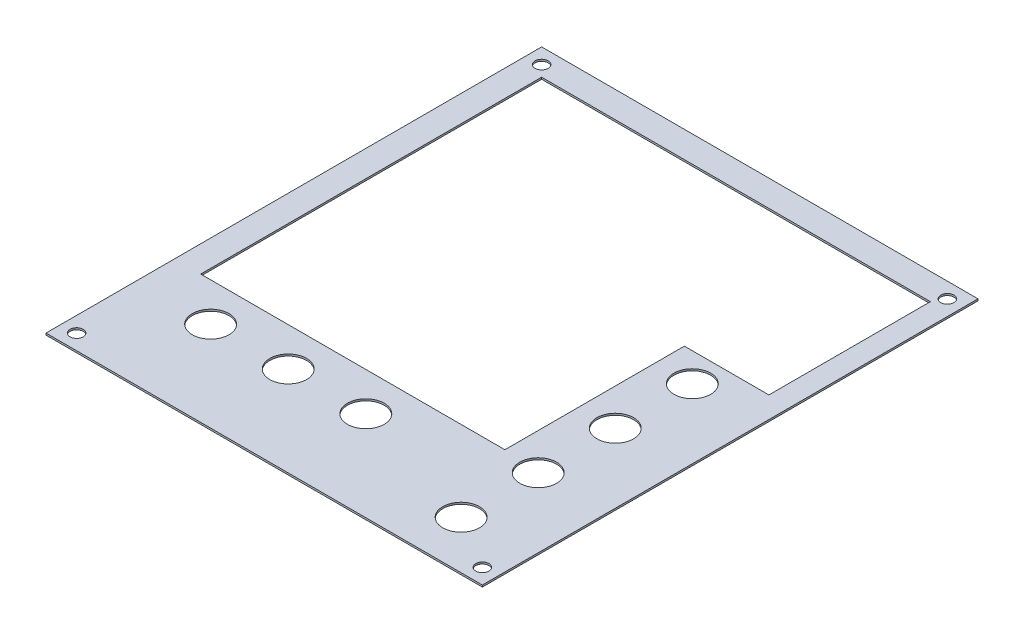
SolidWorks part; units mm, degrees
ref_plane "Front Plane" through (0, 0, 0) normal (0, 0, 1) x (1, 0, 0)
ref_plane "Top Plane" through (0, 0, 0) normal (0, 1, 0) x (1, 0, 0)
ref_plane "Right Plane" through (0, 0, 0) normal (1, 0, 0) x (0, 0, -1)
sketch "Sketch1" plane through (0, 0, 0) normal (0, 1, 0) x (1, 0, 0)
  line L0 (11.302, 19.99) -> (11.302, 8.49) construction
  line L1 (0, 0) -> (77.34, 0) construction
  line L2 (0, 0) -> (0, 88.64) construction
  line L3 (0, 88.64) -> (77.34, 88.64) construction
  line L4 (77.34, 0) -> (77.34, 88.64) construction
  line L5 (6.302, 8.49) -> (16.302, 8.49) construction
  line L6 (6.302, 8.49) -> (6.302, 19.99) construction
  line L7 (6.302, 19.99) -> (16.302, 19.99) construction
  line L8 (16.302, 8.49) -> (16.302, 19.99) construction
  line L9 (21.095, 8.49) -> (31.095, 8.49) construction
  line L10 (21.095, 8.49) -> (21.095, 19.99) construction
  line L11 (21.095, 19.99) -> (31.095, 19.99) construction
  line L12 (31.095, 8.49) -> (31.095, 19.99) construction
  line L13 (35.888, 8.49) -> (45.888, 8.49) construction
  line L14 (35.888, 8.49) -> (35.888, 19.99) construction
  line L15 (35.888, 19.99) -> (45.888, 19.99) construction
  line L16 (45.888, 8.49) -> (45.888, 19.99) construction
  line L17 (62.147, 30.178) -> (71.947, 30.178) construction
  line L18 (62.147, 30.178) -> (62.147, 41.078) construction
  line L19 (62.147, 41.078) -> (71.947, 41.078) construction
  line L20 (71.947, 30.178) -> (71.947, 41.078) construction
  line L21 (62.147, 15.488) -> (71.947, 15.488) construction
  line L22 (62.147, 15.488) -> (62.147, 26.388) construction
  line L23 (62.147, 26.388) -> (71.947, 26.388) construction
  line L24 (71.947, 15.488) -> (71.947, 26.388) construction
  line L25 (62.147, 0.798) -> (71.947, 0.798) construction
  line L26 (62.147, 0.798) -> (62.147, 11.698) construction
  line L27 (62.147, 11.698) -> (71.947, 11.698) construction
  line L28 (71.947, 0.798) -> (71.947, 11.698) construction
  line L29 (62.147, 44.868) -> (71.947, 44.868) construction
  line L30 (62.147, 44.868) -> (62.147, 55.768) construction
  line L31 (62.147, 55.768) -> (71.947, 55.768) construction
  line L32 (71.947, 44.868) -> (71.947, 55.768) construction
  line L33 (26.095, 19.99) -> (26.095, 8.49) construction
  line L34 (40.888, 19.99) -> (40.888, 8.49) construction
  line L35 (67.047, 11.698) -> (67.047, 0.798) construction
  line L36 (67.047, 26.388) -> (67.047, 15.488) construction
  line L37 (67.047, 41.078) -> (67.047, 30.178) construction
  line L38 (67.047, 55.768) -> (67.047, 44.868) construction
  line L40 (-2.92, 91.56) -> (80.26, 91.56)
  line L41 (-2.92, 91.56) -> (-2.92, -2.92)
  line L42 (-2.92, -2.92) -> (80.26, -2.92)
  line L43 (80.26, 91.56) -> (80.26, -2.92)
  line L44 (2.08, 86.56) -> (60.08, 86.56)
  line L45 (2.08, 86.56) -> (2.08, 21.56)
  line L46 (2.08, 21.56) -> (60.08, 21.56)
  line L47 (60.08, 55.768) -> (60.08, 21.56)
  line L48 (60.08, 86.56) -> (76.1929, 86.56)
  line L50 (60.08, 55.768) -> (76.1929, 55.768)
  line L51 (76.1929, 86.56) -> (76.1929, 55.768)
  circle A0 centre (0, 88.64) radius 1.25
  circle A1 centre (77.34, 88.64) radius 1.25
  circle A2 centre (77.34, 0) radius 1.25
  circle A3 centre (0, 0) radius 1.25
  circle A4 centre (11.302, 14.24) radius 3.5
  circle A5 centre (26.095, 14.24) radius 3.5
  circle A6 centre (40.888, 14.24) radius 3.5
  circle A7 centre (67.047, 6.248) radius 3.5
  circle A8 centre (67.047, 20.938) radius 3.5
  circle A9 centre (67.047, 35.628) radius 3.5
  circle A10 centre (67.047, 50.318) radius 3.5
  dimension "D3" = 2.5
  dimension "D4" = 2.5
  dimension "D5" = 2.5
  dimension "D6" = 2.5
  dimension "D30" = 7
  dimension "D31" = 7
  dimension "D32" = 7
  dimension "D33" = 7
  dimension "D34" = 7
  dimension "D35" = 7
  dimension "D36" = 7
  dimension "D37" = 2.92
  dimension "D38" = 2.92
  dimension "D39" = 2.92
  dimension "D40" = 2.92
  dimension "D1" = 88.64
  dimension "D2" = 77.34
  dimension "D7" = 10
  dimension "D8" = 11.5
  dimension "D9" = 10
  dimension "D10" = 11.5
  dimension "D11" = 10
  dimension "D12" = 11.5
  dimension "D13" = 4.793
  dimension "D14" = 4.793
  dimension "D15" = 6.302
  dimension "D16" = 8.49
  dimension "D17" = 9.8
  dimension "D18" = 10.9
  dimension "D19" = 9.8
  dimension "D20" = 10.9
  dimension "D21" = 9.8
  dimension "D22" = 10.9
  dimension "D23" = 9.8
  dimension "D24" = 10.9
  dimension "D25" = 3.79
  dimension "D26" = 3.79
  dimension "D27" = 3.79
  dimension "D28" = 62.147
  dimension "D29" = 0.798
  dimension "D41" = 5
  dimension "D42" = 5
  dimension "D43" = 58
  dimension "D44" = 65
  dimension "D45" = 30.792
  dimension "D46" = 16.1129
  dimension "D47" = 74.1129
extrude "Boss-Extrude1" add sketch "Sketch1" along normal blind 0.35
